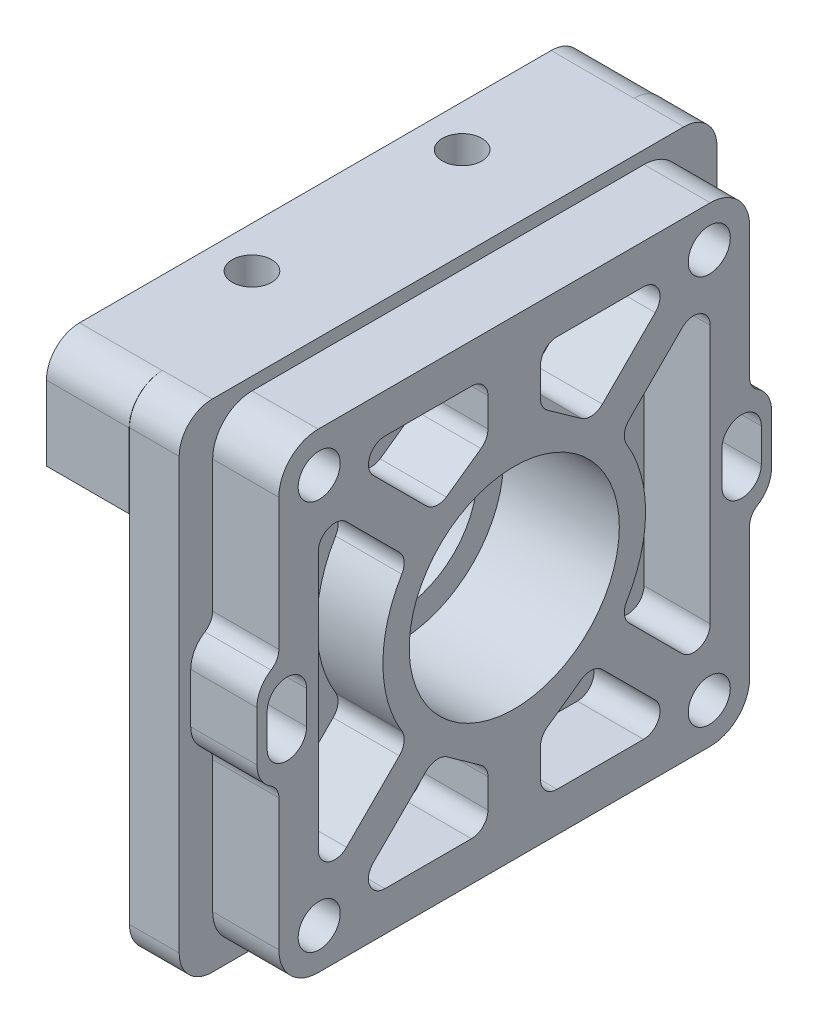
SolidWorks part; units mm, degrees
ref_plane "Front Plane" through (0, 0, 0) normal (0, 0, 1) x (1, 0, 0)
ref_plane "Top Plane" through (0, 0, 0) normal (0, 1, 0) x (1, 0, 0)
ref_plane "Right Plane" through (0, 0, 0) normal (1, 0, 0) x (0, 0, -1)
ref_plane "Plane1" through (10, 0, 0) normal (1, 0, 0) x (0, 0, -1)
sketch "Sketch2" plane through (10, 0, 0) normal (1, 0, 0) x (0, 0, -1)
  line L0 (-23.5712, 23.5712) -> (23.5712, 23.5712) construction
  line L1 (-23.5712, -23.5712) -> (23.5712, -23.5712) construction
  line L2 (23.5712, 23.5712) -> (23.5712, -23.5712) construction
  line L3 (-23.5712, -23.5712) -> (-23.5712, 23.5712) construction
  line L4 (25.1, 2) -> (25.1, -2)
  line L5 (29.8625, -2) -> (29.8625, 2)
  line L6 (-29.8625, -2) -> (-29.8625, 2)
  line L7 (-28.5, 30) -> (28.5, 30)
  line L8 (-32.5, 26) -> (-32.5, -26)
  line L9 (-28.5, -30) -> (28.5, -30)
  line L10 (32.5, 26) -> (32.5, -26)
  line L11 (-32.5, 30) -> (32.5, -30) construction
  line L12 (-32.5, -30) -> (32.5, 30) construction
  line L14 (0, 0) -> (0, 18.4014) construction
  line L15 (-25.1, 2) -> (-25.1, -2)
  circle A0 centre (0, 0) radius 23.5712 construction
  circle A1 centre (-23.5712, 23.5712) radius 2.54
  circle A2 centre (23.5712, 23.5712) radius 2.54
  circle A3 centre (23.5712, -23.5712) radius 2.54
  circle A4 centre (0, 0) radius 12.7
  arc A5 (-32.5, -26) -> (-28.5, -30) centre (-28.5, -26) ccw
  arc A6 (28.5, -30) -> (32.5, -26) centre (28.5, -26) ccw
  arc A7 (32.5, 26) -> (28.5, 30) centre (28.5, 26) ccw
  arc A8 (-32.5, 26) -> (-28.5, 30) centre (-28.5, 26) cw
  circle A9 centre (0, 0) radius 27.4812 construction
  arc A10 (-29.8625, -2) -> (-25.1, -2) centre (-27.4813, -2) ccw
  arc A11 (29.8625, 2) -> (25.1, 2) centre (27.4813, 2) ccw
  circle A12 centre (-23.5712, -23.5712) radius 2.54
  arc A13 (29.8625, -2) -> (25.1, -2) centre (27.4813, -2) cw
  arc A14 (-29.8625, 2) -> (-25.1, 2) centre (-27.4812, 2) cw
  point P0 (0, 0)
  point P10 (0, 0)
  point P36 (-29.8625, 0)
  point P44 (-25.1, 0)
  point P46 (25.1, 0)
  point P47 (29.8625, 0)
  dimension "D3" = 4
  dimension "D1" = 25.4
  dimension "D2" = 65
  dimension "D4" = 54.9625
  dimension "D6" = 47.1424
  dimension "D7" = 5.08
  dimension "D5" = 60
sketch "Sketch3" plane through (0, 0, 0) normal (1, 0, 0) x (0, 0, -1)
  line L0 (32.46, 26) -> (32.46, 17)
  line L1 (-32.54, 26) -> (-32.54, 17)
  line L2 (-32.54, 17) -> (-22.0852, 17)
  line L3 (28.46, 30) -> (-28.54, 30)
  line L4 (0, 0) -> (0, 35.3161) construction
  line L5 (-9.365, 1.7384) -> (-6.2433, 18.4309)
  line L6 (32.46, 17) -> (22.0117, 17)
  line L7 (6.2402, 18.4476) -> (9.3603, 1.7634)
  line L8 (-20.15, 15.5048) -> (-11.1542, -18.9836)
  line L9 (20.0744, 15.497) -> (11.2424, -18.9314)
  line L11 (-23.5712, 23.5712) -> (23.5712, 23.5712) construction
  line L12 (-23.5712, 23.5712) -> (-23.5712, -23.5712) construction
  line L13 (-23.5712, -23.5712) -> (23.5712, -23.5712) construction
  line L14 (23.5712, 23.5712) -> (23.5712, -23.5712) construction
  line L15 (-23.5712, 23.5712) -> (23.5712, -23.5712) construction
  line L16 (-23.5712, -23.5712) -> (23.5712, 23.5712) construction
  line L19 (6.2172, -9.525) -> (-6.2664, -9.525) construction
  arc A0 (-22.0852, 17) -> (-20.15, 15.5048) centre (-22.0852, 15) cw
  arc A1 (-11.1542, -18.9836) -> (11.2424, -18.9314) centre (0, 0) ccw
  arc A2 (22.0117, 17) -> (20.0744, 15.497) centre (22.0117, 15) ccw
  circle A3 centre (-23.5712, 23.5712) radius 2.54
  circle A4 centre (23.5712, 23.5712) radius 2.54
  arc A5 (32.46, 26) -> (28.46, 30) centre (28.46, 26) ccw
  arc A6 (-6.2433, 18.4309) -> (6.2402, 18.4476) centre (0, 17.272) cw
  arc A8 (-28.54, 30) -> (-32.54, 26) centre (-28.54, 26) ccw
  arc A10 (9.3603, 1.7634) -> (-9.365, 1.7384) centre (0, 0) cw
  point P38 (-6.35, 23.622)
  point P41 (6.35, 23.622)
  dimension "D1" = 2
  dimension "D3" = 47.1424
  dimension "D5" = 4
  dimension "D2" = 2
  dimension "D4" = 47.1424
  dimension "D7" = 9.525
extrude "Boss-Extrude1" add sketch "Sketch3" along normal blind 10
extrude "Boss-Extrude2" add sketch "Sketch2" along normal blind 6
ref_plane "Plane2" through (16, 0, 0) normal (1, 0, 0) x (0, 0, -1)
sketch "Sketch4" plane through (16, 0, 0) normal (1, 0, 0) x (0, 0, -1)
  line L0 (-28.448, -7.7717) -> (-28.448, -23.6855)
  line L1 (28.448, -7.7717) -> (28.448, -23.6855)
  line L2 (28.448, 23.6855) -> (28.448, 7.7717)
  line L3 (-23.6855, 28.448) -> (23.6855, 28.448)
  line L4 (0, 0) -> (0, 18.6733) construction
  line L5 (0, 0) -> (-17.5025, 0) construction
  line L6 (-28.448, 23.6855) -> (-28.448, 7.7717)
  line L7 (-23.6855, -28.448) -> (23.6855, -28.448)
  line L8 (-15.6242, 23.6855) -> (-5.175, 23.6855)
  line L9 (23.6855, 15.6242) -> (23.6855, -15.6242)
  line L10 (17.0384, -20.2713) -> (10.6544, -13.8873)
  line L11 (-23.6855, -15.6242) -> (-23.6855, 15.6242)
  line L12 (-20.2713, 17.0384) -> (-13.8873, 10.6544)
  line L13 (-17.0384, 20.2713) -> (-10.6544, 13.8873)
  line L14 (17.0384, 20.2713) -> (10.6544, 13.8873)
  line L15 (20.2713, 17.0384) -> (13.8873, 10.6544)
  line L16 (20.2713, -17.0384) -> (13.8873, -10.6544)
  line L17 (5.175, -23.6855) -> (15.6242, -23.6855)
  line L18 (3.175, -21.6855) -> (3.175, -18.2001)
  line L19 (-20.2713, -17.0384) -> (-13.8873, -10.6544)
  line L20 (-3.175, 21.6855) -> (-3.175, 18.2001)
  line L21 (-8.2063, 13.5894) -> (-4.0157, 16.5704)
  line L22 (5.175, 23.6855) -> (15.6242, 23.6855)
  line L23 (3.175, 21.6855) -> (3.175, 18.2001)
  line L24 (8.2063, 13.5894) -> (4.0157, 16.5704)
  line L25 (8.2063, -13.5894) -> (4.0157, -16.5704)
  line L26 (17.0384, -20.2713) -> (10.6544, -13.8873) [skipped]
  line L27 (-17.0384, -20.2713) -> (-10.6544, -13.8873) [skipped]
  line L28 (-3.175, -21.6855) -> (-3.175, -18.2001)
  line L29 (-8.2063, -13.5894) -> (-4.0157, -16.5704)
  line L30 (-17.0384, -20.2713) -> (-10.6544, -13.8873)
  line L31 (-15.6242, -23.6855) -> (-5.175, -23.6855)
  line L32 (-31.1, 3) -> (-31.1, -3)
  line L33 (-23.5712, -23.5712) -> (23.5712, -23.5712) construction
  line L34 (-23.5712, -23.5712) -> (-23.5712, 23.5712) construction
  line L35 (-23.5712, 23.5712) -> (23.5712, 23.5712) construction
  line L36 (23.5712, -23.5712) -> (23.5712, 23.5712) construction
  line L37 (-23.5712, -23.5712) -> (23.5712, 23.5712) construction
  line L38 (-23.5712, 23.5712) -> (23.5712, -23.5712) construction
  line L39 (25.1, 2) -> (25.1, -2)
  line L40 (29.8625, 2) -> (29.8625, -2)
  line L42 (31.1, 3) -> (31.1, -3)
  line L43 (-29.8625, -2) -> (-29.8625, 2)
  line L45 (-29.8625, 0) -> (-25.1, 0) construction
  line L47 (-25.1, 2) -> (-25.1, -2)
  circle A0 centre (0, 0) radius 12.7
  arc A1 (-29.8625, -2) -> (-25.1, -2) centre (-27.4813, -2) ccw
  circle A2 centre (23.5712, 23.5712) radius 2.54
  circle A3 centre (-23.5712, 23.5712) radius 2.54
  arc A4 (31.1, -3) -> (29.392, -6.0732) centre (27.4813, -3) cw
  arc A5 (-23.6855, 28.448) -> (-28.448, 23.6855) centre (-23.6855, 23.6855) ccw
  arc A6 (23.6855, 28.448) -> (28.448, 23.6855) centre (23.6855, 23.6855) cw
  arc A7 (23.6855, -28.448) -> (28.448, -23.6855) centre (23.6855, -23.6855) ccw
  arc A8 (-23.6855, -28.448) -> (-28.448, -23.6855) centre (-23.6855, -23.6855) cw
  arc A9 (31.1, 3) -> (29.392, 6.0732) centre (27.4813, 3) ccw
  arc A10 (-31.1, -3) -> (-29.392, -6.0732) centre (-27.4813, -3) ccw
  arc A11 (-31.1, 3) -> (-29.392, 6.0732) centre (-27.4812, 3) cw
  arc A12 (-29.8625, 2) -> (-25.1, 2) centre (-27.4813, 2) cw
  arc A13 (-29.392, 6.0732) -> (-28.448, 7.7717) centre (-30.448, 7.7717) ccw
  arc A14 (29.392, 6.0732) -> (28.448, 7.7717) centre (30.448, 7.7717) cw
  arc A15 (-28.448, -7.7717) -> (-29.392, -6.0732) centre (-30.448, -7.7717) ccw
  arc A16 (29.392, -6.0732) -> (28.448, -7.7717) centre (30.448, -7.7717) ccw
  arc A17 (29.8625, -2) -> (25.1, -2) centre (27.4813, -2) cw
  circle A18 centre (-23.6855, 23.6855) radius 4.7625 construction
  arc A19 (20.2713, 17.0384) -> (23.6855, 15.6242) centre (21.6855, 15.6242) cw
  arc A20 (-13.5894, 8.2063) -> (-13.5894, -8.2063) centre (0, 0) ccw
  arc A21 (-3.175, 21.6855) -> (-5.175, 23.6855) centre (-5.175, 21.6855) ccw
  arc A22 (3.175, 21.6855) -> (5.175, 23.6855) centre (5.175, 21.6855) cw
  circle A23 centre (0, 0) radius 15.875 construction
  circle A24 centre (0, 0) radius 1.27 construction
  arc A25 (15.6242, 23.6855) -> (17.0384, 20.2713) centre (15.6242, 21.6855) cw
  arc A26 (13.5894, 8.2063) -> (13.8873, 10.6544) centre (15.3015, 9.2402) cw
  arc A27 (-13.5894, 8.2063) -> (-13.8873, 10.6544) centre (-15.3015, 9.2402) ccw
  arc A28 (-8.2063, 13.5894) -> (-10.6544, 13.8873) centre (-9.2402, 15.3015) cw
  arc A29 (-23.6855, 15.6242) -> (-20.2713, 17.0384) centre (-21.6855, 15.6242) cw
  arc A30 (-17.0384, 20.2713) -> (-15.6242, 23.6855) centre (-15.6242, 21.6855) cw
  arc A31 (8.2063, 13.5894) -> (10.6544, 13.8873) centre (9.2402, 15.3015) ccw
  arc A32 (8.2063, -13.5894) -> (10.6544, -13.8873) centre (9.2402, -15.3015) cw
  arc A33 (13.5894, 8.2063) -> (13.5894, -8.2063) centre (0, 0) cw
  arc A34 (23.6855, -15.6242) -> (20.2713, -17.0384) centre (21.6855, -15.6242) cw
  arc A35 (15.6242, -23.6855) -> (17.0384, -20.2713) centre (15.6242, -21.6855) ccw
  arc A36 (13.5894, -8.2063) -> (13.8873, -10.6544) centre (15.3015, -9.2402) ccw
  arc A37 (-20.2713, -17.0384) -> (-23.6855, -15.6242) centre (-21.6855, -15.6242) cw
  arc A38 (3.175, -21.6855) -> (5.175, -23.6855) centre (5.175, -21.6855) ccw
  arc A39 (-13.5894, -8.2063) -> (-13.8873, -10.6544) centre (-15.3015, -9.2402) cw
  arc A40 (3.175, -18.2001) -> (4.0157, -16.5704) centre (5.175, -18.2001) cw
  arc A41 (-3.175, 18.2001) -> (-4.0157, 16.5704) centre (-5.175, 18.2001) cw
  arc A42 (3.175, 18.2001) -> (4.0157, 16.5704) centre (5.175, 18.2001) ccw
  arc A43 (8.2063, -13.5894) -> (10.6544, -13.8873) centre (9.2402, -15.3015) cw [skipped]
  arc A44 (-8.2063, -13.5894) -> (-10.6544, -13.8873) centre (-9.2402, -15.3015) ccw [skipped]
  arc A45 (17.0384, -20.2713) -> (15.6242, -23.6855) centre (15.6242, -21.6855) cw [skipped]
  arc A46 (-15.6242, -23.6855) -> (-17.0384, -20.2713) centre (-15.6242, -21.6855) cw [skipped]
  arc A47 (-8.2063, -13.5894) -> (-10.6544, -13.8873) centre (-9.2402, -15.3015) ccw
  arc A48 (-3.175, -18.2001) -> (-4.0157, -16.5704) centre (-5.175, -18.2001) ccw
  arc A49 (-3.175, -21.6855) -> (-5.175, -23.6855) centre (-5.175, -21.6855) cw
  arc A50 (-17.0384, -20.2713) -> (-15.6242, -23.6855) centre (-15.6242, -21.6855) ccw
  arc A51 (29.8625, 2) -> (25.1, 2) centre (27.4813, 2) ccw
  circle A53 centre (23.5712, -23.5712) radius 2.54
  circle A54 centre (-23.5712, -23.5712) radius 2.54
  point P55 (3.175, 23.6855)
  dimension "D2" = 2
  dimension "D3" = 4
  dimension "D4" = 2
  dimension "D5" = 31.75
  dimension "D6" = 47.1424
  dimension "D7" = 2
  dimension "D8" = 2
  dimension "D9" = 2
  dimension "D10" = 2
  dimension "D11" = 2
  dimension "D12" = 2
  dimension "D13" = 2
  dimension "D15" = 2
  dimension "D16" = 2
  dimension "D17" = 2
  dimension "D14" = 47.1424
extrude "Boss-Extrude3" add sketch "Sketch4" along normal blind 8
ref_plane "Plane3" through (0, 30, 0) normal (0, 1, 0) x (-1, 0, 0)
sketch "Sketch5" plane through (0, 30, 0) normal (0, 1, 0) x (-1, 0, 0)
  line L0 (0, 0) -> (-10, 0) construction
  line L1 (-10, 55) -> (-10, -55) construction
  line L4 (-5, -12.7) -> (-5, 12.7) construction
  circle A0 centre (-5, 0) radius 12.7 construction
  circle A1 centre (-5, -12.7) radius 2.3812
  circle A2 centre (-5, 12.7) radius 2.3812
  dimension "D1" = 25.4
  dimension "D2" = 4.7625
extrude "Cut-Extrude1" cut sketch "Sketch5" against normal blind 70 contours A2 | A1
ref_plane "Plane4" through (16, 0, 0) normal (1, 0, 0) x (0, 0, -1)
ref_plane "Plane5" through (24, 0, 0) normal (1, 0, 0) x (0, 0, -1)
sketch "Sketch6" plane through (24, 0, 0) normal (1, 0, 0) x (0, 0, -1)
  circle A0 centre (-23.5712, 23.5712) radius 2.54
  circle A1 centre (-23.5712, 23.5712) radius 4.9241
  circle A2 centre (23.5712, 23.5712) radius 2.54
  circle A3 centre (23.5712, 23.5712) radius 4.9241
  circle A4 centre (23.5712, -23.5712) radius 2.54
  circle A5 centre (23.5712, -23.5712) radius 4.9241
  circle A6 centre (-23.5712, -23.5712) radius 2.54
  circle A7 centre (-23.5712, -23.5712) radius 4.9241
  dimension "D1" = 4
